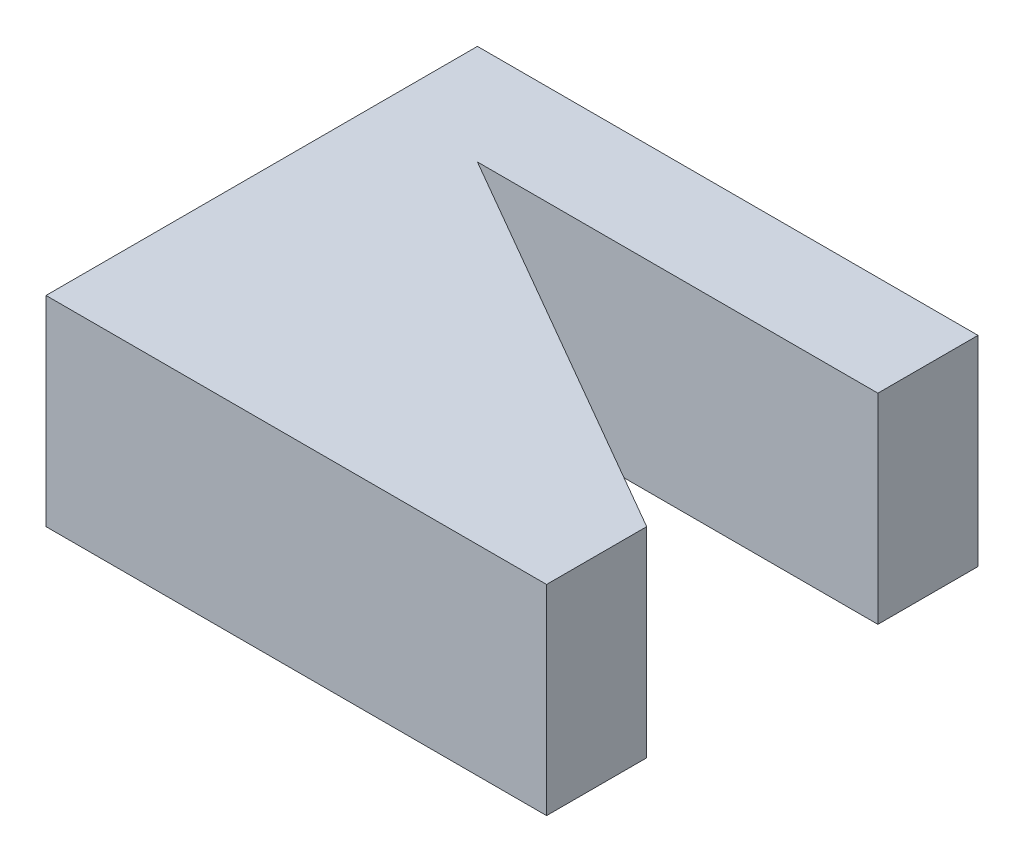
SolidWorks part; units mm, degrees
ref_plane "Přední rovina" through (0, 0, 0) normal (0, 0, 1) x (1, 0, 0)
ref_plane "Horní rovina" through (0, 0, 0) normal (0, 1, 0) x (1, 0, 0)
ref_plane "Pravá rovina" through (0, 0, 0) normal (1, 0, 0) x (0, 0, -1)
sketch "Sketch1" plane through (0, 0, 0) normal (0, 1, 0) x (1, 0, 0)
  line L0 (0, 0) -> (0, -43.094)
  line L1 (0, -43.094) -> (50, -43.094)
  line L2 (50, -43.094) -> (50, -33.094)
  line L5 (10, -10) -> (50, -10)
  line L6 (50, -10) -> (50, 0)
  line L7 (50, 0) -> (0, 0)
  line L8 (10, -10) -> (50, -33.094)
  dimension "D1" = 10
  dimension "D2" = 10
  dimension "D3" = 40
  dimension "D4" = 30
  dimension "D5" = 10
extrude "Boss-Extrude1" add sketch "Sketch1" along normal blind 20 contours L8 L2 L1 L0 L7 L6 L5
equation "\"Angle\"= 30"
equation "\"L\"= 40"
equation "\"D3@Sketch1\"=\"L\""
equation "\"D4@Sketch1\"=\"Angle\""
